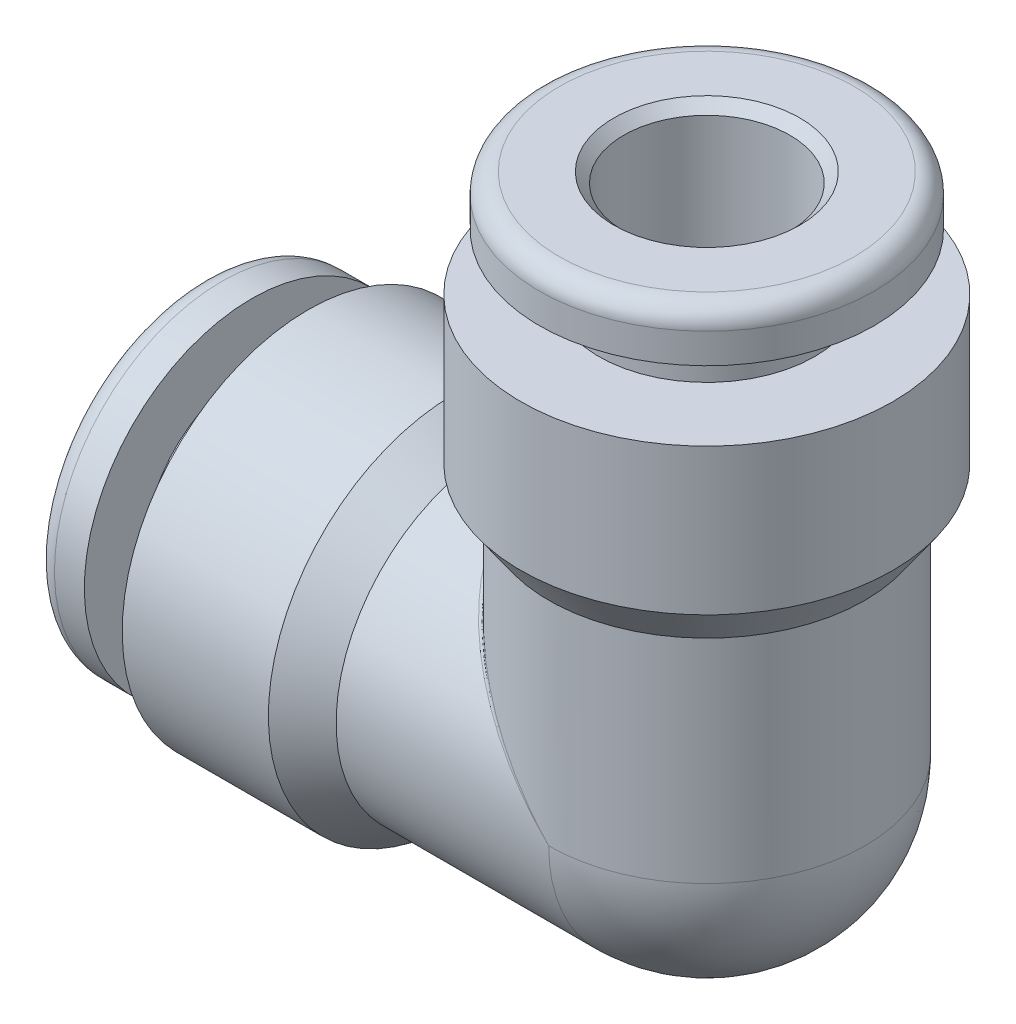
SolidWorks part; units mm, degrees
ref_plane "Front Plane" through (0, 0, 0) normal (0, 0, 1) x (1, 0, 0)
ref_plane "Top Plane" through (0, 0, 0) normal (0, 1, 0) x (1, 0, 0)
ref_plane "Right Plane" through (0, 0, 0) normal (1, 0, 0) x (0, 0, -1)
sketch "Sketch1" plane through (0, 0, 0) normal (0, 0, 1) x (1, 0, 0)
  line L0 (0, 0) -> (-19.304, 0) construction
  line L1 (-15.24, 7.112) -> (-9.652, 7.112)
  line L2 (-18.542, 6.4008) -> (-17.399, 6.4008)
  line L3 (-19.304, 5.6388) -> (-19.304, 3.556)
  line L4 (-18.923, 3.175) -> (-9.652, 3.175)
  line L5 (0, 6.0452) -> (0, 2.6987)
  line L6 (-19.304, 3.556) -> (-18.923, 3.175)
  line L7 (-17.399, 6.4008) -> (-17.399, 4.1275)
  line L8 (-17.399, 4.1275) -> (-15.24, 4.1275)
  line L9 (-15.24, 7.112) -> (-15.24, 4.1275)
  line L10 (-9.652, 3.175) -> (-9.652, 2.6987)
  line L11 (-9.652, 2.6987) -> (0, 2.6987)
  line L12 (0, 6.0452) -> (-8.1285, 6.0452)
  line L13 (-8.1285, 6.0452) -> (-9.652, 7.112)
  line L16 (-7.112, 0) -> (7.112, 0) construction
  line L17 (0, 0) -> (0, 19.304) construction
  arc A0 (-18.542, 6.4008) -> (-19.304, 5.6388) centre (-18.542, 5.6388) ccw
  point P5 (-19.304, 3.175)
  point P14 (-19.304, 6.4008)
  dimension "D3" = 0.762
  dimension "D1" = 1.905
  dimension "D2" = 2.159
  dimension "G" = 14.224
  dimension "D4" = 12.8016
  dimension "D5" = 8.255
  dimension "D6" = 5.3975
  dimension "D9" = 35
  dimension "D10" = 9.652
  dimension "D11" = 12.0904
  dimension "D7" = 14.224
  dimension "D12" = 9.652
revolve "Revolve1" add sketch "Sketch1" angle 360 about L0
sketch "Sketch2" plane through (0, 0, 0) normal (1, 0, 0) x (0, 0, -1)
  line L0 (-6.0452, 0) -> (6.0452, 0) construction
  circle A0 centre (0, 0) radius 6.0452 construction
  circle A1 centre (0, 0) radius 6.0452 construction
ref_axis "Axis1" through (0, 0, -6.0452) along (0, 0, 1)
pattern_circular "CirPattern1" count 2 over 90 about axis through (0, 0, -6.0452) along (0, 0, 1) of "Revolve1"
sketch "Sketch5" plane through (0, 0, 0) normal (0, -1, 0) x (1, 0, 0)
  circle A0 centre (0, 0) radius 2.6987
  arc A1 (0, -2.6987) -> (0, 2.6987) centre (0, 0) ccw construction
extrude "Cut-Extrude3" cut sketch "Sketch5" against normal through all
sketch "Sketch6" plane through (0, 0, 0) normal (1, 0, 0) x (0, 0, -1)
  circle A0 centre (0, 0) radius 2.6987
  arc A1 (-2.6987, 0) -> (2.6987, 0) centre (0, 0) ccw construction
extrude "Cut-Extrude4" cut sketch "Sketch6" against normal through all
sketch "Sketch7" plane through (0, 0, 0) normal (1, 0, 0) x (0, 0, -1)
  line L0 (2.6987, 0) -> (-2.6987, 0) construction
  line L2 (-2.6987, 0) -> (-6.0452, 0)
  line L3 (6.0452, 0) -> (2.6987, 0)
  line L4 (-2.6987, 0) -> (-6.0452, 0)
  line L5 (6.0452, 0) -> (2.6987, 0)
  arc A2 (-6.0452, 0) -> (6.0452, 0) centre (0, 0) ccw
  arc A3 (-2.6987, 0) -> (2.6987, 0) centre (0, 0) ccw
  arc A4 (-6.0452, 0) -> (6.0452, 0) centre (0, 0) ccw
  arc A5 (-2.6987, 0) -> (2.6987, 0) centre (0, 0) ccw
  dimension "D1" = 0
revolve "Revolve2" add sketch "Sketch7" angle 90 about L0
fillet "Fillet1" radius 0.254 1 edges at (-6.0452, 6.0452, 0)
equation "\"D4@Sketch1\" = \"G@Sketch1\"*.9"
equation "\"D5@Sketch1\" = \"tube od@Sketch1\"*1.3"
equation "\"D6@Sketch1\" = \"tube od@Sketch1\"*.85"
equation "\"D10@Sketch1\" = \"L@Sketch1\"*.5"
equation "\"D11@Sketch1\" = \"G@Sketch1\"*.85"
equation "\"D7@Sketch1\" = \"G@Sketch1\""
equation "\"D12@Sketch1\" = \"L@Sketch1\" * 0.5"
